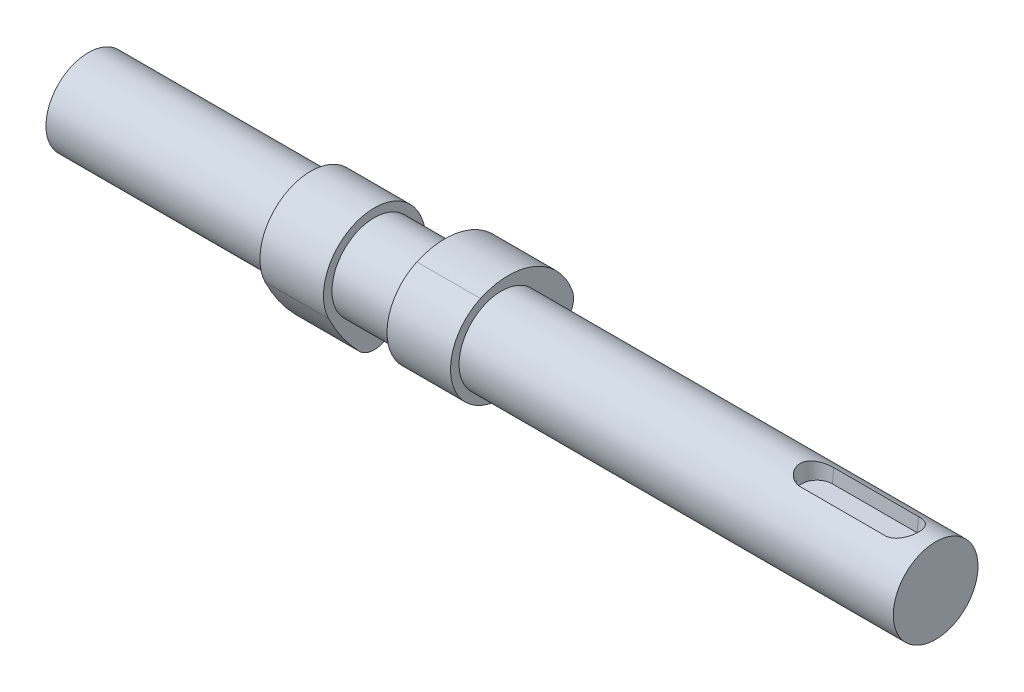
SolidWorks part; units mm, degrees
ref_plane "Front Plane" through (0, 0, 0) normal (0, 0, 1) x (1, 0, 0)
ref_plane "Top Plane" through (0, 0, 0) normal (0, 1, 0) x (1, 0, 0)
ref_plane "Right Plane" through (0, 0, 0) normal (1, 0, 0) x (0, 0, -1)
sketch "Sketch1" plane through (0, 0, 0) normal (1, 0, 0) x (0, 0, -1)
  circle A0 centre (0, 0) radius 10
  dimension "D1" = 20
extrude "Boss-Extrude1" add sketch "Sketch1" along normal blind 125 and the other way blind 75
sketch "Sketch2" plane through (0, 0, 0) normal (1, 0, 0) x (0, 0, -1)
  arc A0 (-4.9508, 10.9311) -> (5.2781, -10.7769) centre (0, 0) ccw
  arc A1 (-4.9508, 10.9311) -> (16.747, 1.6562) centre (1.6503, -3.6437) cw
  arc A2 (16.747, 1.6562) -> (15.5071, -3.5923) centre (12.0293, 0) cw
  arc A3 (15.5071, -3.5923) -> (5.2781, -10.7769) centre (-12.3157, 25.1461) cw
  dimension "D1" = 5
  dimension "D2" = 24
  dimension "D3" = 16
  dimension "D4" = 40
  dimension "D5" = 12.5
extrude "Boss-Extrude2" add sketch "Sketch2" along normal mid plane 15 from offset 15
ref_plane "Plane1" through (0, 0, 0) normal (1, 0, 0) x (0, 0, -1)
mirror "Mirror3" about plane through (0, 0, 0) normal (1, 0, 0) of "Boss-Extrude2"
split "Split1" trim tools "Plane1" bodies to split 109 resulting bodies 110 111
move or copy body "Body-Move/Copy4" bodies to move or copy 111 copy no rotation origin (0, 0, 0) rotation axis (-1, 0, 0) rotation angle 90
combine bodies "Combine1" operation type add bodies to combine 112 110
sketch "Sketch5" plane through (0, 0, 0) normal (0, 1, 0) x (1, 0, 0)
  line L0 (97, 0) -> (117, 0) construction
  line L1 (97, 4) -> (117, 4)
  line L2 (97, -4) -> (117, -4)
  line L3 (125, -10) -> (125, 10) construction
  arc A0 (97, 4) -> (97, -4) centre (97, 0) ccw
  arc A1 (117, -4) -> (117, 4) centre (117, 0) ccw
  point P3 (107, 0)
  dimension "D1" = 4
  dimension "D2" = 20
  dimension "D3" = 8
extrude "Cut-Extrude1" cut sketch "Sketch5" against normal blind 4 draft 5 from offset 10
